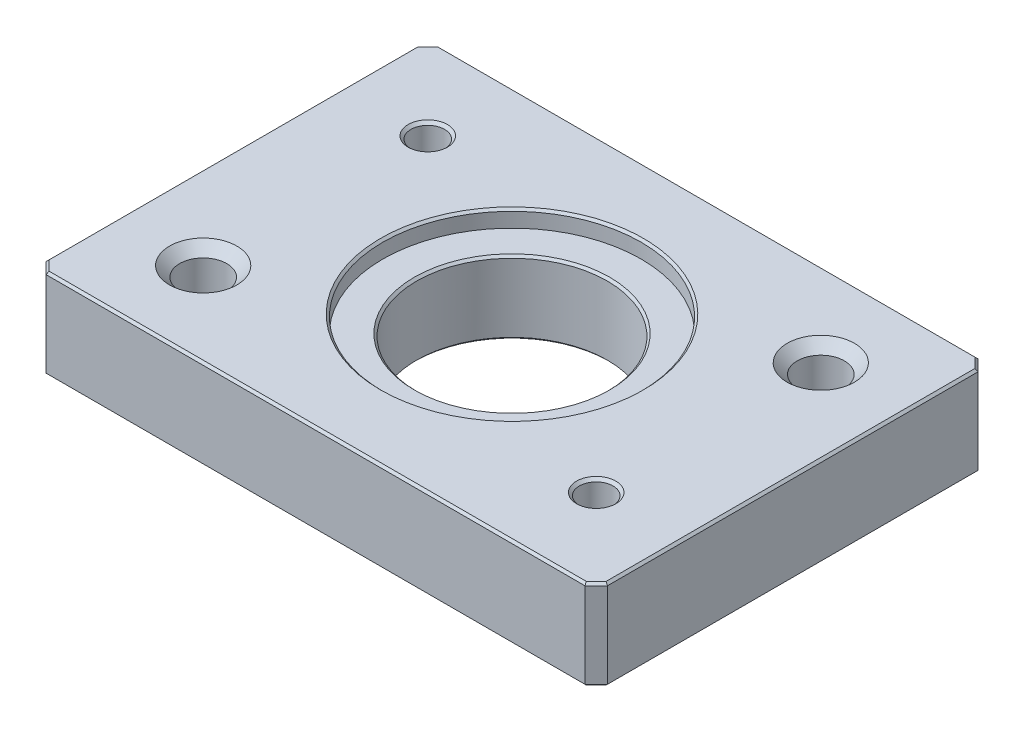
SolidWorks part; units mm, degrees
material "Plain Carbon Steel"
ref_plane "Front Plane" through (0, 0, 0) normal (0, 0, 1) x (1, 0, 0)
ref_plane "Top Plane" through (0, 0, 0) normal (0, 1, 0) x (1, 0, 0)
ref_plane "Right Plane" through (0, 0, 0) normal (1, 0, 0) x (0, 0, -1)
sketch "Sketch1" plane through (0, 0, 0) normal (0, 1, 0) x (1, 0, 0)
  line L1 (-17.5, -10) -> (17.5, -10) construction
  line L2 (-17.5, -10) -> (-17.5, 10) construction
  line L3 (-17.5, 10) -> (17.5, 10) construction
  line L4 (17.5, -10) -> (17.5, 10) construction
  line L5 (-17.5, -10) -> (17.5, 10) construction
  line L6 (-17.5, 10) -> (17.5, -10) construction
  line L7 (25, -17.5) -> (-25, -17.5)
  line L8 (25, -17.5) -> (25, 17.5)
  line L9 (25, 17.5) -> (-25, 17.5)
  line L10 (-25, -17.5) -> (-25, 17.5)
  line L11 (25, -17.5) -> (-25, 17.5) construction
  line L12 (25, 17.5) -> (-25, -17.5) construction
  circle A0 centre (-17.5, 10) radius 7.5 construction
  circle A1 centre (0, 0) radius 8.5
  point P0 (0, 0)
  point P6 (0, 0)
  dimension "D4" = 17
  dimension "D1" = 35
  dimension "D2" = 20
  dimension "D3" = 35
extrude "Boss-Extrude1" add sketch "Sketch1" along normal blind 8
hole_wizard "Ø3.0mm Dowel Hole1" positions "Sketch2" profile "Sketch3" hole size "Ø3.0" standard "ANSI Metric" end condition through all
sketch "Sketch2" plane through (0, 8, 0) normal (0, 1, 0) x (1, 0, 0)
  point P0 (-17.5, 10)
  point P3 (17.5, -10)
sketch "Sketch3" plane through (-17.5, 8, -10) normal (1, 0, 0) x (0, 0, 1)
  line L0 (0, 0) -> (0, 8)
  line L1 (0, 8) -> (1.75, 8)
  line L2 (1.5, 7.75) -> (1.5, 0.25)
  line L3 (1.5, 0.25) -> (1.75, 0)
  line L5 (1.75, 0) -> (0, 0)
  line L6 (-1.5, 0.25) -> (-1.75, 0) construction
  line L7 (1.75, 8) -> (1.5, 7.75)
  line L8 (-1.75, 8) -> (-1.5, 7.75) construction
  line L11 (0, -6.35) -> (0, 107.95) construction
  dimension "Thru Hole Dia." = 3
  dimension "Thru Hole Depth" = 8
  dimension "Near C'Sink Dia." = 3.5
  dimension "Near C'Sink Angle" = 90
  dimension "Far C'Sink Dia." = 3.5
  dimension "Far C'Sink Angle" = 90
hole_wizard "M5x0.8 Tapped Hole1" positions "Sketch4" profile "Sketch5" tap size "M5x0.8" standard "ANSI Metric" end condition through all
sketch "Sketch4" plane through (0, 8, 0) normal (0, 1, 0) x (1, 0, 0)
  point P0 (17.5, 10)
  point P3 (-17.5, -10)
sketch "Sketch5" plane through (17.5, 8, -10) normal (1, 0, 0) x (0, 0, 1)
  line L0 (0, 0) -> (0, 8)
  line L1 (0, 8) -> (3, 8)
  line L2 (2.1, 7.1) -> (2.1, 0.9)
  line L3 (2.1, 0.9) -> (3, 0)
  line L5 (3, 0) -> (0, 0)
  line L6 (-2.1, 0.9) -> (-3, 0) construction
  line L7 (3, 8) -> (2.1, 7.1)
  line L8 (-3, 8) -> (-2.1, 7.1) construction
  line L11 (0, -6.35) -> (0, 107.95) construction
  dimension "Thru Tap Drill Dia." = 4.2
  dimension "Thru Tap Drill Depth" = 8
  dimension "Near C'Sink Dia." = 6
  dimension "Near C'Sink Angle" = 90
  dimension "Far C'Sink Dia." = 6
  dimension "Far C'Sink Angle" = 90
sketch "Sketch6" plane through (0, 8, 0) normal (0, 1, 0) x (1, 0, 0)
  circle A0 centre (0, 0) radius 11.5
  circle A1 centre (0, 0) radius 8.5 construction
  dimension "D1" = 3
extrude "Cut-Extrude1" cut sketch "Sketch6" against normal blind 1.5
chamfer "Chamfer1" distance 1 4 edges at (25, 4, -17.5) (25, 4, 17.5) (-25, 4, -17.5) (-25, 4, 17.5)
chamfer "Chamfer2" distance 0.2 19 edges at (0, 0, 8.5) (-24.5, 0, -17) (-25, 0, 0) (-24.5, 0, 17) (0, 0, 17.5) (24.5, 0, 17) (25, 0, 0) (24.5, 0, -17) (0, 0, -17.5) (24.5, 8, 17) (0, 8, 17.5) (-24.5, 8, 17) (-25, 8, 0) (-24.5, 8, -17) (0, 8, -17.5) (24.5, 8, -17) (25, 8, 0) (0, 6.5, 8.5) (0, 8, 11.5)
